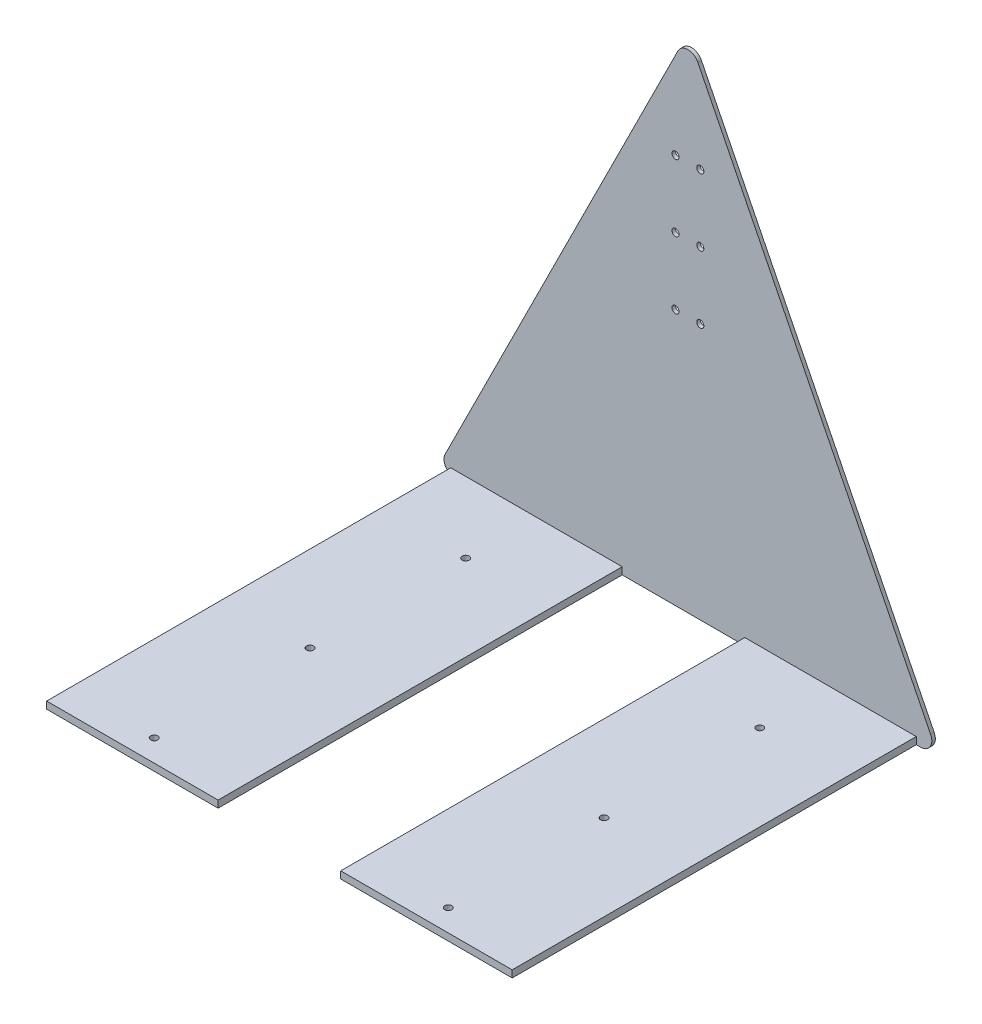
SolidWorks part; units mm, degrees
material "Malleable Cast Iron"
ref_plane "Front Plane" through (0, 0, 0) normal (0, 0, 1) x (1, 0, 0)
ref_plane "Top Plane" through (0, 0, 0) normal (0, 1, 0) x (1, 0, 0)
ref_plane "Right Plane" through (0, 0, 0) normal (1, 0, 0) x (0, 0, -1)
sketch "Sketch1" plane through (0, 0, 0) normal (0, 0, 1) x (1, 0, 0)
  line L0 (0, 0) -> (0, 22860.3449) construction
  line L1 (-454.3751, 21951.5343) -> (-11061.85, 735.1724)
  line L2 (-10607.4749, 0) -> (10607.4749, 0)
  line L3 (11061.85, 735.1724) -> (454.3751, 21951.5343)
  line L4 (-564.515, 17780) -> (564.515, 17780) construction
  circle A0 centre (-564.515, 11684) radius 161.29
  circle A1 centre (-564.515, 14732) radius 161.29
  circle A2 centre (-564.515, 17780) radius 161.29
  circle A3 centre (564.515, 17780) radius 161.29
  circle A4 centre (564.515, 14732) radius 161.29
  circle A5 centre (564.515, 11684) radius 161.29
  arc A6 (-454.3751, 21951.5343) -> (454.3751, 21951.5343) centre (0, 21724.3619) cw
  arc A7 (-10607.4749, 0) -> (-11061.85, 735.1724) centre (-10607.4749, 508) cw
  arc A8 (10607.4749, 0) -> (11061.85, 735.1724) centre (10607.4749, 508) ccw
  point P17 (0, 17780)
  point P18 (0, 0)
  point P24 (-11429.4117, 0)
  point P27 (11429.4117, 0)
  point P28 (11039.602, 240.9228)
  point P29 (-11039.602, 240.9228)
  point P30 (0, 0)
  point P31 (0, 0)
  point P32 (0, 0)
  dimension "D4" = 322.58
  dimension "D5" = 322.58
  dimension "D6" = 322.58
  dimension "D7" = 322.58
  dimension "D8" = 322.58
  dimension "D9" = 322.58
  dimension "D2" = 508
  dimension "D14" = 508
  dimension "D16" = 508
  dimension "D17" = 23720.298
  dimension "D18" = 23720.298
  dimension "D3" = 22079.204
  dimension "D10" = 11684
  dimension "D11" = 3048
  dimension "D12" = 3048
  dimension "D13" = 1129.03
  dimension "D15" = 3048
extrude "Boss-Extrude2" add sketch "Sketch1" along normal blind 161.29
ref_plane "Plane2" through (0, 0, 0) normal (0, -1, 0) x (-1, 0, 0)
sketch "Sketch2" plane through (0, 0, 0) normal (0, -1, 0) x (-1, 0, 0)
  line L0 (-11115.4749, -161.29) -> (-10607.4749, -161.29) construction
  line L1 (10607.4749, -161.29) -> (-10607.4749, -161.29) construction
  line L2 (-10407.0689, -161.29) -> (-2593.0129, -161.29)
  line L3 (-10407.0689, -161.29) -> (-10407.0689, -18576.29)
  line L4 (-10407.0689, -18576.29) -> (-2593.0129, -18576.29)
  line L5 (-2593.0129, -161.29) -> (-2593.0129, -18576.29)
  line L6 (0, 0) -> (0, -8745.8889) construction
  line L7 (2994.9871, -161.29) -> (10809.0431, -161.29)
  line L8 (2994.9871, -161.29) -> (2994.9871, -18576.29)
  line L9 (2994.9871, -18576.29) -> (10809.0431, -18576.29)
  line L10 (10809.0431, -161.29) -> (10809.0431, -18576.29)
  line L11 (6902.0151, -18576.29) -> (6902.0151, -161.29) construction
  line L12 (-6500.0409, -18576.29) -> (-6500.0409, -161.29) construction
  circle A0 centre (-6500.0409, -17580.61) radius 161.29
  circle A1 centre (-6500.0409, -10483.85) radius 161.29
  circle A2 centre (-6500.0409, -3387.09) radius 161.29
  circle A9 centre (6902.0151, -3387.09) radius 161.29
  circle A10 centre (6902.0151, -10483.85) radius 161.29
  circle A11 centre (6902.0151, -17580.61) radius 161.29
  point P21 (0, 0)
  point P28 (-10861.4749, -161.29)
  dimension "D7" = 322.58
  dimension "D8" = 322.58
  dimension "D9" = 322.58
  dimension "D10" = 2
  dimension "D1" = 7814.056
  dimension "D2" = 7814.056
  dimension "D3" = 18415
  dimension "D4" = 18415
  dimension "D5" = 5588
  dimension "D6" = 454.406
  dimension "D13" = 995.68
  dimension "D14" = 7096.76
  dimension "D15" = 7096.76
extrude "Boss-Extrude3" add sketch "Sketch2" against normal blind 322.58
scale "Scale1" bodies to scale 102 105 104 scale about centroid uniform scaling yes scale factor 0.03937
